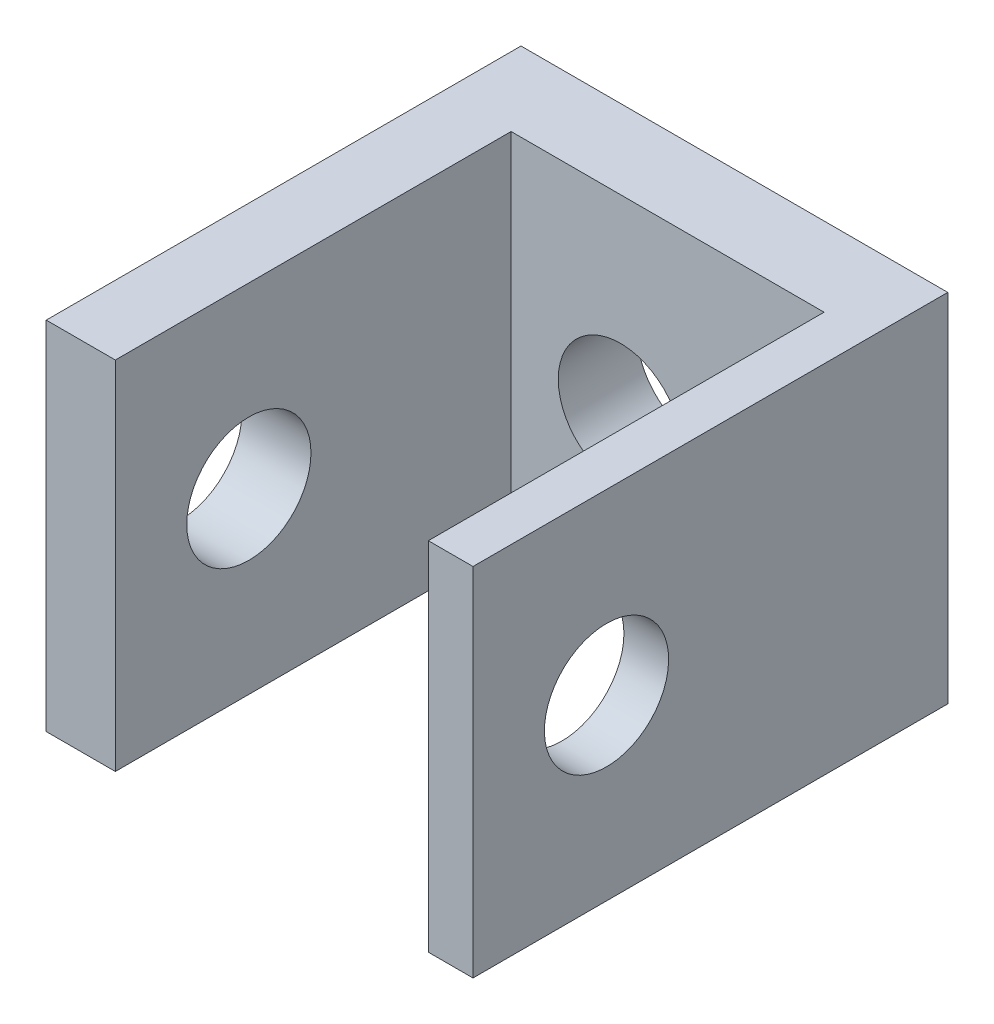
SolidWorks part; units mm, degrees
ref_plane "Front Plane" through (0, 0, 0) normal (0, 0, 1) x (1, 0, 0)
ref_plane "Top Plane" through (0, 0, 0) normal (0, 1, 0) x (1, 0, 0)
ref_plane "Right Plane" through (0, 0, 0) normal (1, 0, 0) x (0, 0, -1)
sketch "Sketch1" plane through (0, 0, 0) normal (0, 0, 1) x (1, 0, 0)
  line L1 (6.6016, -495.03) -> (6.6016, 140.1662) construction
  line L2 (-2.0016, -495.03) -> (-2.0016, 140.3245) construction
  line L3 (6.6016, 13.6852) -> (-2.0016, 13.6852) construction
  line L4 (2.3, 13.6852) -> (2.3, -10.0196) construction
  line L5 (10, 7.6832) -> (10, -6.6639)
  line L6 (10, 9) -> (10, 3.3) construction
  line L7 (10, -3.3) -> (10, -9) construction
  line L8 (10, 7.6832) -> (-7.18, 7.6832)
  line L9 (-7.18, 7.6832) -> (-7.18, -6.6639)
  line L10 (-7.18, -6.6639) -> (10, -6.6639)
  circle A0 centre (0, 0) radius 2.5
  point P0 (0, 0)
  dimension "D1" = 5
  dimension "D2" = 9.48
extrude "Boss-Extrude1" add sketch "Sketch1" along normal blind 3.18
sketch "Sketch2" plane through (0, 0, 3.18) normal (0, 0, 1) x (1, 0, 0)
  line L0 (10, 7.6832) -> (-7.18, 7.6832) construction
  line L1 (10, -6.6639) -> (8.2016, -6.6639)
  line L2 (10, -6.6639) -> (10, 7.6832)
  line L3 (10, 7.6832) -> (8.2016, 7.6832)
  line L4 (8.2016, -6.6639) -> (8.2016, 7.6832)
  line L5 (-7.18, -6.6639) -> (10, -6.6639) construction
  line L6 (-7.18, 7.6832) -> (-4.3984, 7.6832)
  line L7 (-7.18, 7.6832) -> (-7.18, -6.6639)
  line L8 (-7.18, -6.6639) -> (-4.3984, -6.6639)
  line L9 (-4.3984, 7.6832) -> (-4.3984, -6.6639)
  line L10 (8.2016, -9.7881) -> (8.2016, 11.2119) construction
  dimension "D2" = 12.6
extrude "Boss-Extrude2" add sketch "Sketch2" along normal up to vertex (15.9325 mm away)
sketch "Sketch3" plane through (10, 0, 0) normal (1, 0, 0) x (0, 0, -1)
  line L0 (-13.7375, -487.03) -> (-13.7375, -434.0767) construction
  line L1 (-19.1125, 0.5097) -> (-13.7375, 0.5097) construction
  line L2 (-19.1125, -6.6639) -> (-19.1125, 7.6832) construction
  circle A0 centre (-13.7375, 0.5097) radius 2.5
  dimension "D1" = 5
extrude "Cut-Extrude1" cut sketch "Sketch3" against normal through all
